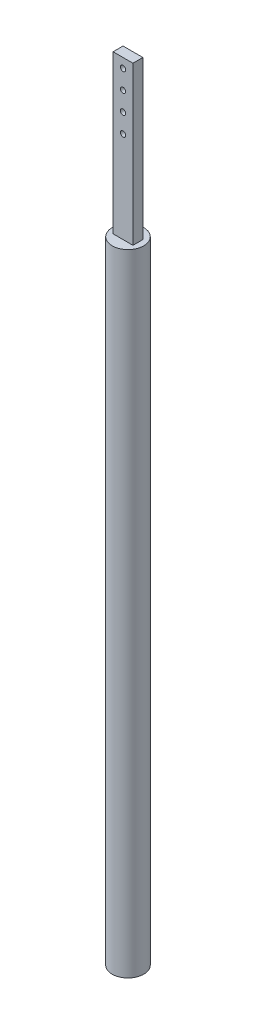
SolidWorks part; units mm, degrees
ref_plane "Front Plane" through (0, 0, 0) normal (0, 0, 1) x (1, 0, 0)
ref_plane "Top Plane" through (0, 0, 0) normal (0, 1, 0) x (1, 0, 0)
ref_plane "Right Plane" through (0, 0, 0) normal (1, 0, 0) x (0, 0, -1)
sketch "Sketch1" plane through (0, 0, 0) normal (0, 1, 0) x (1, 0, 0)
  circle A0 centre (0, 0) radius 3.175
  dimension "D1" = 3.175
extrude "Boss-Extrude1" add sketch "Sketch1" along normal blind 127 contours A0
sketch "Sketch4" plane through (0, 127, 0) normal (0, 1, 0) x (1, 0, 0)
  line L0 (-2, 1) -> (-2, -1)
  line L1 (-2, -1) -> (2, -1)
  line L2 (2, -1) -> (2, 1)
  line L3 (2, 1) -> (-2, 1)
  point P0 (0, 0)
  dimension "D1" = 4
  dimension "D2" = 1
  dimension "D3" = 1
extrude "Boss-Extrude2" add sketch "Sketch4" along normal blind 31.75
sketch "Sketch5" plane through (0, 0, -1) normal (0, 0, -1) x (-1, 0, 0)
  line L2 (-2, 158.75) -> (2, 158.75) construction
  circle A0 centre (0, 156.845) radius 0.5334
  circle A1 centre (0, 153.035) radius 0.5334
  circle A2 centre (0, 149.225) radius 0.5334
  circle A3 centre (0, 145.415) radius 0.5334
  point P5 (0, 158.75)
  dimension "D1" = 1.0668
  dimension "D3" = 1.905
  dimension "D2" = 4
  dimension "D4" = 3.81
extrude "Cut-Extrude1" cut sketch "Sketch5" against normal blind 2 contours A1 | A2 | A3
